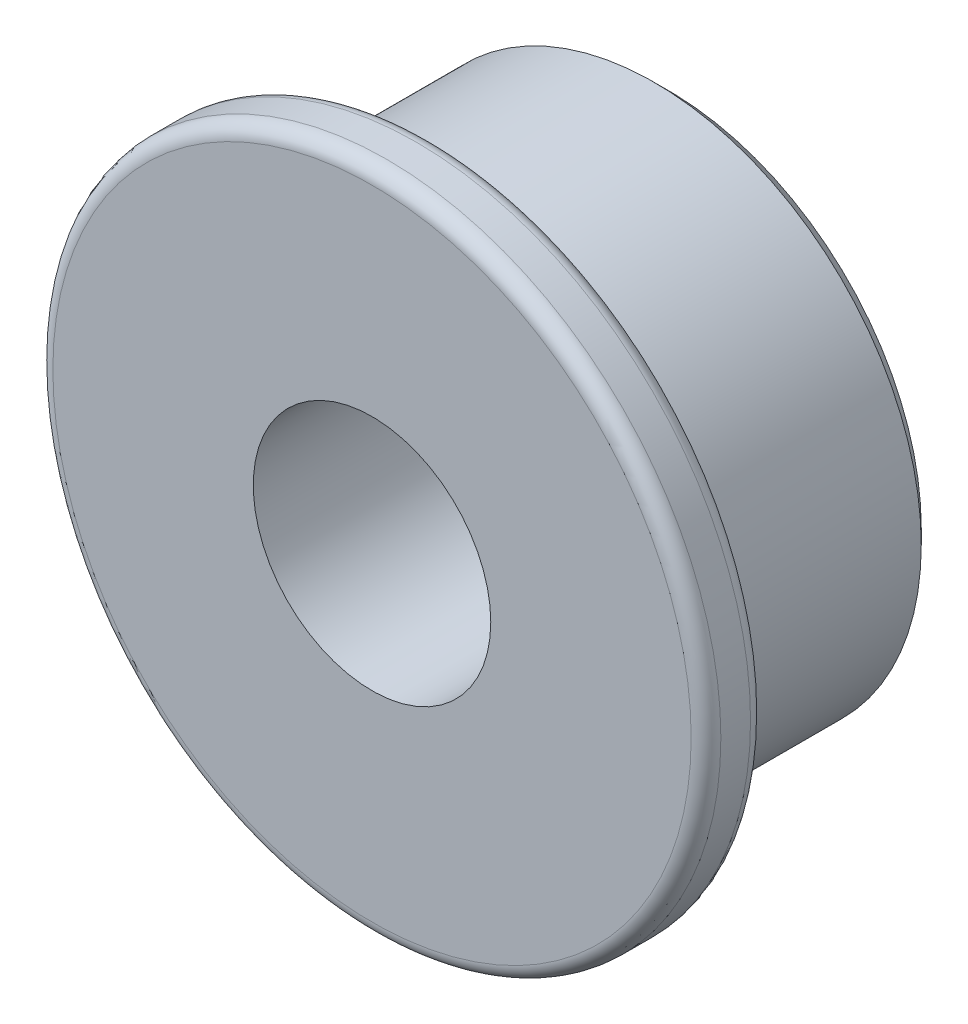
SolidWorks part; units mm, degrees
ref_plane "Front Plane" through (0, 0, 0) normal (0, 0, 1) x (1, 0, 0)
ref_plane "Top Plane" through (0, 0, 0) normal (0, 1, 0) x (1, 0, 0)
ref_plane "Right Plane" through (0, 0, 0) normal (1, 0, 0) x (0, 0, -1)
sketch "Sketch1" plane through (0, 0, 0) normal (0, 0, 1) x (1, 0, 0)
  circle A0 centre (0, 0) radius 9
  circle A1 centre (0, 0) radius 4
  dimension "D1" = 18
  dimension "D2" = 8
extrude "Boss-Extrude1" add sketch "Sketch1" against normal blind 8
sketch "Sketch2" plane through (0, 0, 0) normal (0, 0, 1) x (1, 0, 0)
  circle A0 centre (0, 0) radius 11.25
  circle A1 centre (0, 0) radius 4
  circle A2 centre (0, 0) radius 4 construction
  dimension "D1" = 22.5
extrude "Boss-Extrude2" add sketch "Sketch2" along normal blind 2
fillet "Fillet1" radius 0.5 1 edges at (11.25, 0, 2)
fillet "Fillet2" radius 0.5 1 edges at (11.25, 0, 0)
fillet "Fillet3" radius 0.8 1 edges at (9, 0, 0)
chamfer "Chamfer1" distance 0.5 angle 45 1 edges at (9, 0, -8)
